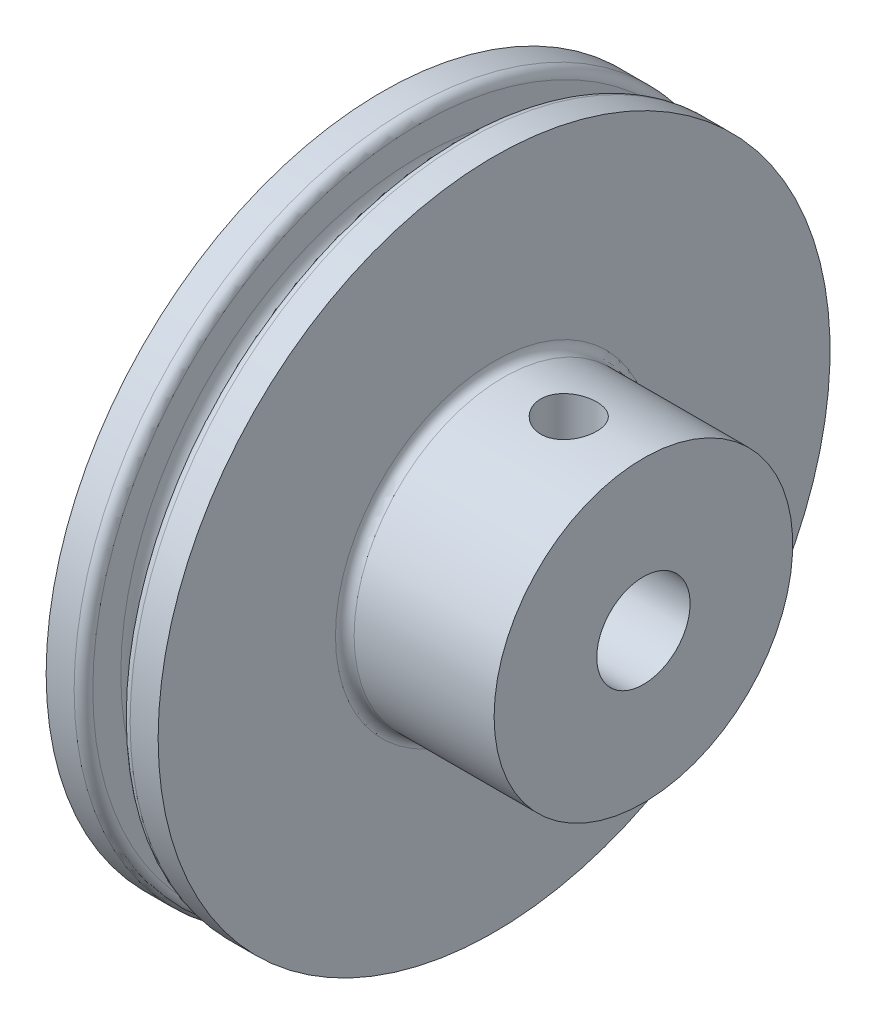
SolidWorks part; units mm, degrees
ref_plane "Front Plane" through (0, 0, 0) normal (0, 0, 1) x (1, 0, 0)
ref_plane "Top Plane" through (0, 0, 0) normal (0, 1, 0) x (1, 0, 0)
ref_plane "Right Plane" through (0, 0, 0) normal (1, 0, 0) x (0, 0, -1)
sketch "Sketch1" plane through (0, 0, 0) normal (0, 0, 1) x (1, 0, 0)
  line L0 (-11.5427, -7.9771) -> (2.4573, -7.9771) construction
  line L1 (-11.5427, 10.0229) -> (-10.0427, 10.0229)
  line L2 (-11.5427, 10.0229) -> (-11.5427, -5.4771)
  line L3 (-11.5427, -5.4771) -> (2.4573, -5.4771)
  line L4 (-5.5427, 10.0229) -> (-5.5427, 0.5229)
  line L5 (2.4573, -5.4771) -> (2.4573, 0.0229)
  line L6 (2.4573, 0.0229) -> (-5.0427, 0.0229)
  line L7 (-7.5427, 9.5229) -> (-7.5427, 8.0229)
  line L8 (-7.0427, 10.0229) -> (-5.5427, 10.0229)
  line L10 (-9.5427, 9.5229) -> (-9.5427, 8.0229)
  arc A0 (-9.5427, 8.0229) -> (-7.5427, 8.0229) centre (-8.5427, 8.0229) ccw
  arc A1 (-9.5427, 9.5229) -> (-10.0427, 10.0229) centre (-10.0427, 9.5229) ccw
  arc A2 (-7.5427, 9.5229) -> (-7.0427, 10.0229) centre (-7.0427, 9.5229) cw
  arc A3 (-5.0427, 0.0229) -> (-5.5427, 0.5229) centre (-5.0427, 0.5229) cw
  point P8 (-8.5427, 16.0229)
  point P15 (-7.5427, 10.0229)
  dimension "D1" = 0.5
  dimension "D2" = 0.5
  dimension "D4" = 0.5
  dimension "D3" = 18
  dimension "D5" = 2.5
revolve "Revolve1" add sketch "Sketch1" angle 360 about L0
sketch "Sketch7" plane through (0, 0, 0) normal (0, 1, 0) x (1, 0, 0)
  line L0 (-5.5427, 0) -> (2.4573, 0) construction
  line L1 (-5.5427, -18) -> (-5.5427, 18) construction
  line L2 (2.4573, -8) -> (2.4573, 8) construction
  circle A0 centre (-1.5427, 0) radius 1.5
extrude "Cut-Extrude3" cut sketch "Sketch7" against normal blind 8 and the other way blind 2
